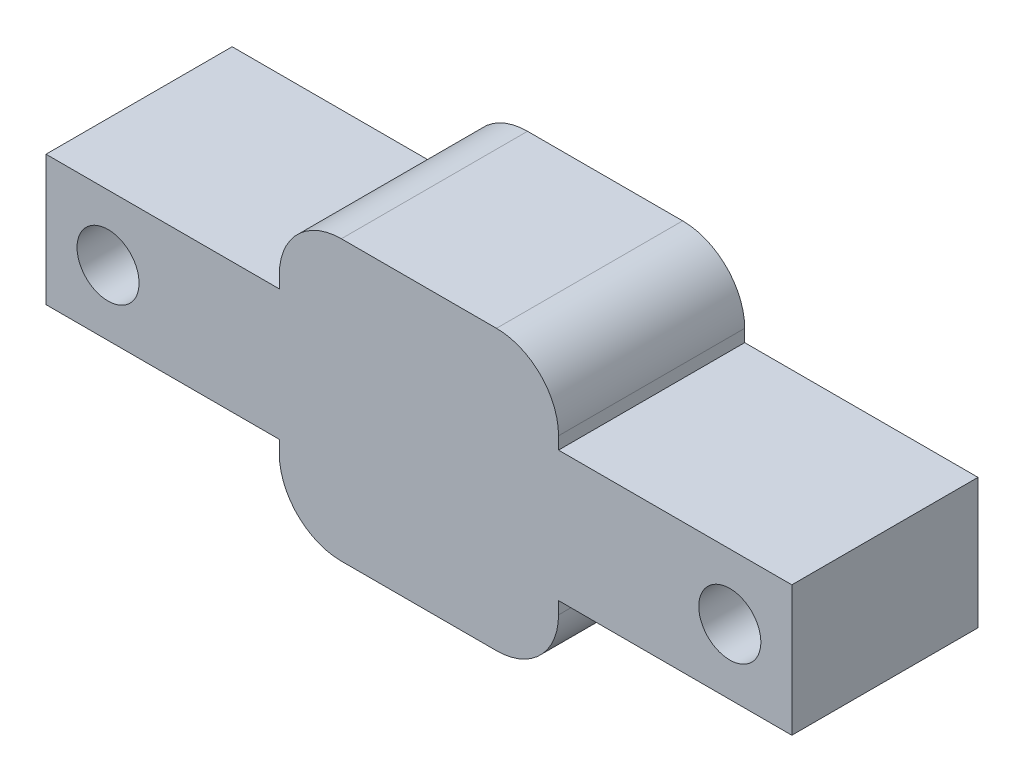
SolidWorks part; units mm, degrees
material "PLA"
ref_plane "Front Plane" through (0, 0, 0) normal (0, 0, 1) x (1, 0, 0)
ref_plane "Top Plane" through (0, 0, 0) normal (0, 1, 0) x (1, 0, 0)
ref_plane "Right Plane" through (0, 0, 0) normal (1, 0, 0) x (0, 0, -1)
sketch "Sketch2" plane through (0, 0, 0) normal (0, 0, 1) x (1, 0, 0)
  line L1 (-14.2875, -14.2875) -> (14.2875, -14.2875)
  line L2 (-14.2875, -14.2875) -> (-14.2875, 14.2875)
  line L3 (-14.2875, 14.2875) -> (14.2875, 14.2875)
  line L4 (14.2875, -14.2875) -> (14.2875, 14.2875)
  line L5 (-14.2875, -14.2875) -> (14.2875, 14.2875) construction
  line L6 (-14.2875, 14.2875) -> (14.2875, -14.2875) construction
  point P0 (0, 0)
  dimension "D1" = 28.575
  dimension "D2" = 28.575
extrude "Boss-Extrude2" add sketch "Sketch2" along normal blind 19.05
sketch "Sketch1" plane through (0, 0, 0) normal (0, 0, 1) x (1, 0, 0)
  circle A1 centre (0, 0) radius 13.335
extrude "Cut-Extrude4" cut sketch "Sketch1" along normal blind 1.5875
fillet "Fillet2" radius 6.35 4 edges at (-14.2875, -14.2875, 9.525) (-14.2875, 14.2875, 9.525) (14.2875, -14.2875, 9.525) (14.2875, 14.2875, 9.525)
sketch "Sketch3" plane through (14.2875, 0, 0) normal (1, 0, 0) x (0, 0, -1)
  line L0 (-19.05, -7.9375) -> (-19.05, 7.9375) construction
  line L1 (-19.05, 6.6675) -> (0, 6.6675)
  line L2 (-19.05, 6.6675) -> (-19.05, -6.6675)
  line L3 (-19.05, -6.6675) -> (0, -6.6675)
  line L4 (0, 6.6675) -> (0, -6.6675)
  line L5 (0, -7.9375) -> (0, 7.9375) construction
  dimension "D1" = 1.27
  dimension "D2" = 1.27
extrude "Boss-Extrude3" add sketch "Sketch3" along normal blind 23.876
sketch "Sketch4" plane through (0, 0, 0) normal (0, 0, -1) x (-1, 0, 0)
  line L0 (-38.1635, -6.6675) -> (-38.1635, 6.6675) construction
  circle A0 centre (-31.8135, 0) radius 3.175
  dimension "D1" = 6.35
  dimension "D2" = 6.35
extrude "Cut-Extrude5" cut sketch "Sketch4" against normal through all both and the other way through all
sketch "Sketch6" plane through (0, 0, 0) normal (0, 0, -1) x (-1, 0, 0)
  circle A0 centre (-31.8135, 0) radius 4.7625
  dimension "D1" = 9.525
extrude "Cut-Extrude6" cut sketch "Sketch6" against normal blind 6.35
mirror "Mirror1" about plane through (0, 0, 0) normal (1, 0, 0) of "Boss-Extrude3", "Cut-Extrude5", "Cut-Extrude6"
sketch "Sketch7" plane through (0, 0, 19.05) normal (0, 0, 1) x (1, 0, 0)
  circle A0 centre (-31.8135, 0) radius 3.175
  circle A1 centre (31.8135, 0) radius 3.175
  dimension "D1" = 6.35
  dimension "D2" = 6.35
equation "\"D2@Sketch3\"=\"D1@Sketch3\""
